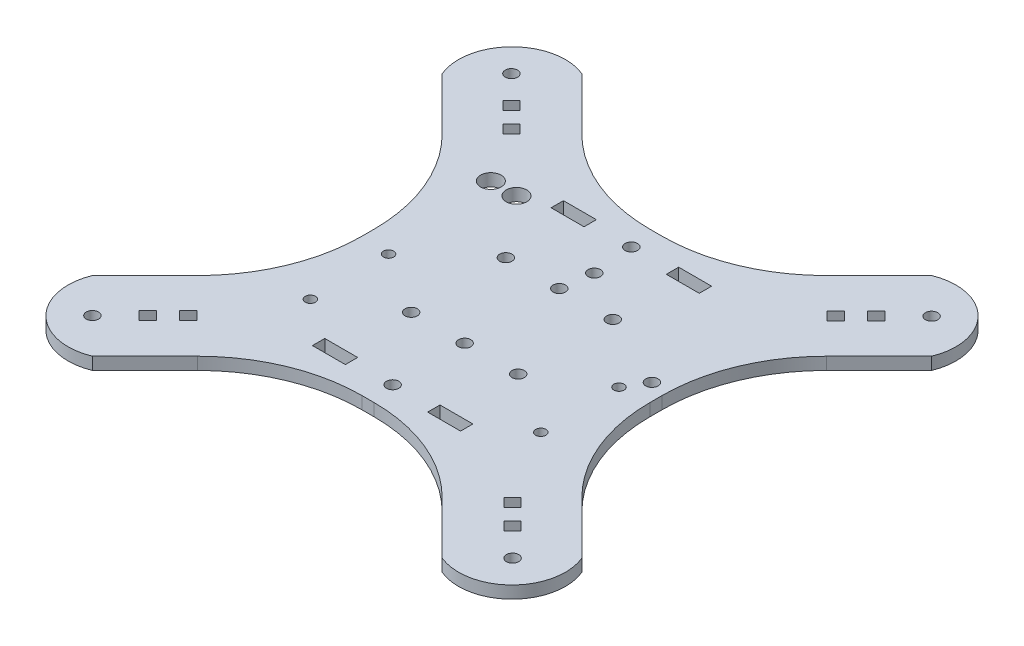
SolidWorks part; units mm, degrees
material "Pinho"
ref_plane "Plano frontal" through (0, 0, 0) normal (0, 0, 1) x (1, 0, 0)
ref_plane "Plano superior" through (0, 0, 0) normal (0, 1, 0) x (1, 0, 0)
ref_plane "Plano direito" through (0, 0, 0) normal (1, 0, 0) x (0, 0, -1)
sketch "Esboço1" plane through (0, 0, 0) normal (0, 1, 0) x (1, 0, 0)
  line L0 (52.3811, 40.4945) -> (65.1312, 27.7444)
  line L2 (121.8478, -29.5) -> (121.8478, -32.5)
  line L3 (129.8478, -32.5) -> (121.8478, -32.5)
  line L4 (129.8478, -29.5) -> (129.8478, -32.5)
  line L5 (110.3869, 33) -> (113.3087, 33)
  line L6 (149.1024, 37.2502) -> (151.2237, 39.3715)
  line L7 (110.3869, -37) -> (113.3087, -37)
  line L8 (146.8486, -3.4601) -> (146.8486, -0.5399)
  line L9 (129.8478, -29.5) -> (121.8478, -29.5)
  line L10 (149.1024, 37.2502) -> (151.2237, 35.1289)
  line L11 (151.2237, 35.1289) -> (153.345, 37.2502)
  line L12 (151.2237, 39.3715) -> (153.345, 37.2502)
  line L14 (154.0522, 42.2) -> (156.1735, 44.3213)
  line L15 (154.0522, 42.2) -> (156.1735, 40.0786)
  line L16 (93.8478, -29.5) -> (101.8478, -29.5)
  line L17 (156.1735, 40.0786) -> (158.2948, 42.2)
  line L18 (101.8478, 25.5) -> (101.8478, 28.5)
  line L19 (93.8478, 28.5) -> (101.8478, 28.5)
  line L20 (93.8478, 25.5) -> (93.8478, 28.5)
  line L21 (156.1735, 44.3213) -> (158.2948, 42.2)
  line L22 (93.8478, 25.5) -> (101.8478, 25.5)
  line L26 (129.8478, 25.5) -> (121.8478, 25.5)
  line L27 (129.8478, 25.5) -> (129.8478, 28.5)
  line L28 (129.8478, 28.5) -> (121.8478, 28.5)
  line L29 (121.8478, 25.5) -> (121.8478, 28.5)
  line L30 (69.3525, 57.4659) -> (82.1026, 44.7157)
  line L31 (76.847, -3.4601) -> (76.847, -0.5399)
  line L33 (67.5221, 44.3213) -> (65.4008, 42.2)
  line L34 (67.5221, 40.0786) -> (65.4008, 42.2)
  line L35 (69.6434, 42.2) -> (67.5221, 40.0786)
  line L36 (69.6434, 42.2) -> (67.5221, 44.3213)
  line L37 (72.4718, 39.3715) -> (70.3505, 37.2502)
  line L38 (72.4718, 35.1289) -> (70.3505, 37.2502)
  line L39 (74.5932, 37.2502) -> (72.4718, 35.1289)
  line L40 (74.5932, 37.2502) -> (72.4718, 39.3715)
  line L41 (67.5221, -44.0786) -> (65.4008, -46.2)
  line L42 (67.5221, -48.3213) -> (65.4008, -46.2)
  line L43 (74.5932, -41.2502) -> (72.4718, -43.3715)
  line L44 (74.5932, -41.2502) -> (72.4718, -39.1289)
  line L45 (72.4718, -39.1289) -> (70.3505, -41.2502)
  line L46 (72.4718, -43.3715) -> (70.3505, -41.2502)
  line L47 (69.6434, -46.2) -> (67.5221, -48.3213)
  line L48 (69.6434, -46.2) -> (67.5221, -44.0786)
  line L51 (156.1735, -48.3213) -> (158.2948, -46.2)
  line L52 (156.1735, -44.0786) -> (158.2948, -46.2)
  line L53 (154.0522, -46.2) -> (156.1735, -44.0786)
  line L54 (154.0522, -46.2) -> (156.1735, -48.3213)
  line L55 (151.2237, -43.3715) -> (153.345, -41.2502)
  line L56 (151.2237, -39.1289) -> (153.345, -41.2502)
  line L57 (149.1024, -41.2502) -> (151.2237, -39.1289)
  line L58 (93.8478, -29.5) -> (93.8478, -32.5)
  line L59 (93.8478, -32.5) -> (101.8478, -32.5)
  line L60 (101.8478, -29.5) -> (101.8478, -32.5)
  line L61 (149.1024, -41.2502) -> (151.2237, -43.3715)
  line L72 (171.3145, -44.4945) -> (158.5643, -31.7444)
  line L74 (69.3525, -61.4659) -> (82.1026, -48.7157)
  line L75 (52.3811, -44.4945) -> (65.1312, -31.7444)
  line L76 (154.3431, -61.4659) -> (141.593, -48.7157)
  line L78 (154.3431, 57.4659) -> (141.593, 44.7157)
  line L79 (171.3145, 40.4945) -> (158.5643, 27.7444)
  circle A0 centre (111.8478, 27) radius 1.5
  circle A1 centre (111.8478, -31) radius 1.5
  arc A2 (69.3525, 57.4659) -> (52.3811, 40.4945) centre (64.4013, 45.4457) ccw
  arc A3 (76.847, -0.5399) -> (65.1312, 27.7444) centre (36.847, -0.5399) ccw
  arc A4 (110.3869, 33) -> (82.1026, 44.7157) centre (110.3869, 73) cw
  circle A5 centre (60.7965, 48.9099) radius 1.5
  circle A6 centre (111.8478, -13.5) radius 1.5
  circle A7 centre (124.8478, -13.5) radius 1.5
  circle A8 centre (98.8478, -13.5) radius 1.5
  circle A9 centre (98.8478, 9.5) radius 1.5
  circle A10 centre (124.8478, 9.5) radius 1.5
  circle A11 centre (111.8478, 9.5) radius 1.5
  circle A12 centre (83.8478, -4) radius 1.25
  circle A13 centre (139.8478, -4) radius 1.25
  arc A14 (154.3431, -61.4659) -> (171.3145, -44.4945) centre (159.2943, -49.4457) ccw
  circle A15 centre (60.7965, -52.9099) radius 1.5
  arc A16 (110.3869, -37) -> (82.1026, -48.7157) centre (110.3869, -77) ccw
  arc A17 (146.8486, -3.4601) -> (158.5643, -31.7444) centre (186.8486, -3.4601) ccw
  arc A18 (113.3087, -37) -> (141.593, -48.7157) centre (113.3087, -77) cw
  arc A19 (76.847, -3.4601) -> (65.1312, -31.7444) centre (36.847, -3.4601) cw
  circle A20 centre (139.8478, -23) radius 1.25
  circle A21 centre (83.8478, -23) radius 1.25
  circle A22 centre (112.8478, 17) radius 1.5
  circle A23 centre (162.8991, -52.9099) radius 1.5
  arc A24 (69.3525, -61.4659) -> (52.3811, -44.4945) centre (64.4013, -49.4457) cw
  circle A25 centre (162.8991, 48.9099) radius 1.5
  arc A26 (113.3087, 33) -> (141.593, 44.7157) centre (113.3087, 73) ccw
  arc A27 (146.8486, -0.5399) -> (158.5643, 27.7444) centre (186.8486, -0.5399) cw
  arc A28 (154.3431, 57.4659) -> (171.3145, 40.4945) centre (159.2943, 45.4457) cw
  circle A29 centre (142.8478, 1) radius 1.5
  circle A30 centre (80.9031, 23.8042) radius 2.5
  circle A31 centre (87.1292, 23.8042) radius 2.5
extrude "Ressalto-extrusão1" add sketch "Esboço1" along normal blind 3
